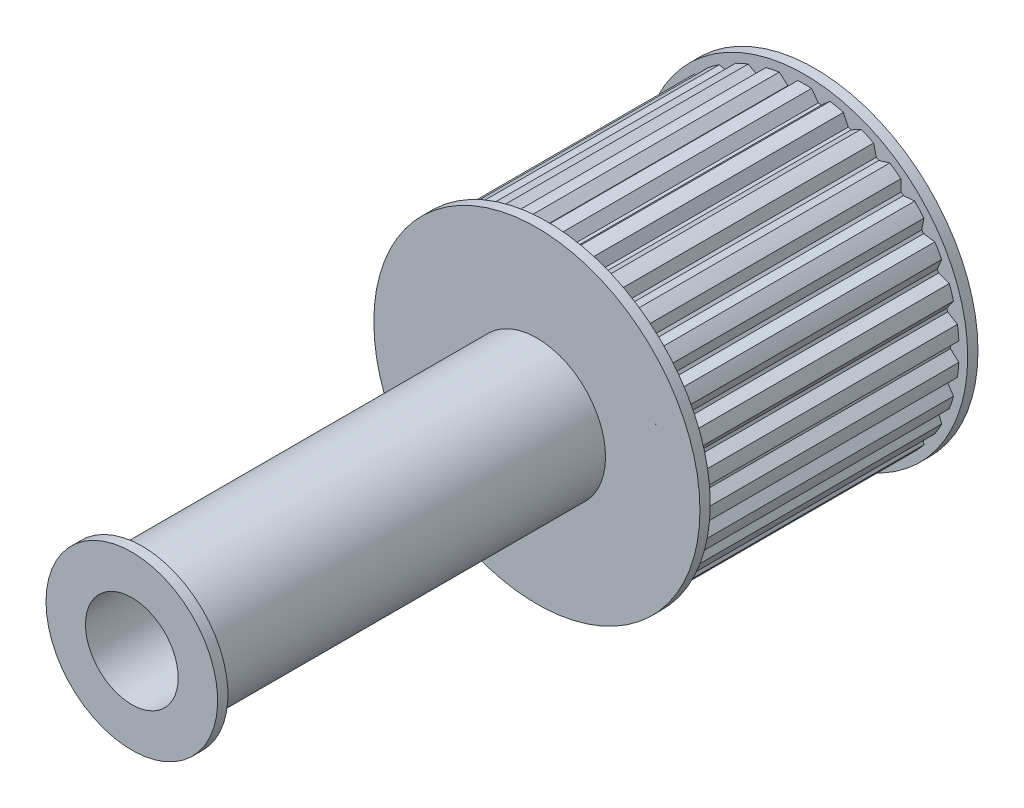
SolidWorks part; units mm, degrees
ref_plane "Front Plane" through (0, 0, 0) normal (0, 0, 1) x (1, 0, 0)
ref_plane "Top Plane" through (0, 0, 0) normal (0, 1, 0) x (1, 0, 0)
ref_plane "Right Plane" through (0, 0, 0) normal (1, 0, 0) x (0, 0, -1)
sketch "Sketch1" plane through (0, 0, 0) normal (0, 0, 1) x (1, 0, 0)
  line L0 (-26.76, 0) -> (36.8516, 0) construction
  line L1 (0, -14.6584) -> (0, 16.5839) construction
  circle A1 centre (0, 0) radius 6.35
  dimension "D2" = 12.7
extrude "Boss-Extrude1" add sketch "Sketch1" along normal blind 0.762
sketch "Sketch3" plane through (0, 0, 0) normal (0, 0, -1) x (-1, 0, 0)
  circle A0 centre (0, 0) radius 5.08
  dimension "D1" = 10.16
extrude "Boss-Extrude2" add sketch "Sketch3" along normal blind 29.21
sketch "Sketch9" plane through (0, 0, -29.21) normal (0, 0, -1) x (-1, 0, 0)
  circle A0 centre (0, 0) radius 5.08
  dimension "D1" = 10.16
curve "Helix/Spiral1" pitch 1.5568 height 28.8008 turns 18.5
sketch "Sketch4" plane through (0, 0, -29.21) normal (0, 0, -1) x (-1, 0, 0)
  circle A0 centre (0, 0.091) radius 12.065
  dimension "D1" = 24.13
extrude "Boss-Extrude3" add sketch "Sketch4" along normal blind 0.762
sketch "Sketch5" plane through (0, 0, -29.972) normal (0, 0, -1) x (-1, 0, 0)
  circle A0 centre (0, 0) radius 10.795
  dimension "D1" = 21.59
extrude "Boss-Extrude4" add sketch "Sketch5" along normal blind 19.05
sketch "Sketch8" plane through (0, 0, -49.022) normal (0, 0, -1) x (-1, 0, 0)
  line L0 (0, 11.43) -> (0, -11.43) construction
  line L1 (-0.508, 11.4187) -> (-1.016, 10.7471)
  line L2 (0.508, 11.4187) -> (1.016, 10.7471)
  line L3 (1.8772, 11.2748) -> (1.2406, 10.7235)
  line L4 (4.1803, 10.6381) -> (3.4431, 10.2312)
  line L5 (6.3008, 9.5365) -> (5.495, 9.2918)
  line L6 (8.1458, 8.0181) -> (7.3068, 7.9462)
  line L7 (9.6349, 6.1493) -> (8.7992, 6.2534)
  line L8 (10.7029, 4.0117) -> (9.9071, 4.2873)
  line L9 (11.3031, 1.6988) -> (10.582, 2.1338)
  line L10 (11.4093, -0.6884) -> (10.7944, -0.1129)
  line L11 (11.0168, -3.0454) -> (10.535, -2.3548)
  line L12 (10.1429, -5.2694) -> (9.8152, -4.4937)
  line L13 (8.8257, -7.2631) -> (8.6665, -6.4362)
  line L14 (7.1227, -8.9393) -> (7.1389, -8.0974)
  line L15 (5.1085, -10.2249) -> (5.2994, -9.4047)
  line L16 (2.871, -11.0636) -> (3.2282, -10.301)
  line L17 (0.508, -11.4187) -> (1.016, -10.7471)
  line L18 (-1.8772, -11.2748) -> (-1.2406, -10.7235)
  line L19 (-4.1803, -10.6381) -> (-3.4431, -10.2312)
  line L20 (-6.3008, -9.5365) -> (-5.495, -9.2918)
  line L21 (-8.1458, -8.0181) -> (-7.3068, -7.9462)
  line L22 (-9.6349, -6.1493) -> (-8.7992, -6.2534)
  line L23 (-10.7029, -4.0117) -> (-9.9071, -4.2873)
  line L24 (-11.3031, -1.6988) -> (-10.582, -2.1338)
  line L25 (-11.4093, 0.6884) -> (-10.7944, 0.1129)
  line L26 (-11.0168, 3.0454) -> (-10.535, 2.3548)
  line L27 (-10.1429, 5.2694) -> (-9.8152, 4.4937)
  line L28 (-8.8257, 7.2631) -> (-8.6665, 6.4362)
  line L29 (-7.1227, 8.9393) -> (-7.1389, 8.0974)
  line L30 (-5.1085, 10.2249) -> (-5.2994, 9.4047)
  line L31 (-2.871, 11.0636) -> (-3.2282, 10.301)
  line L32 (2.871, 11.0636) -> (3.2282, 10.301)
  line L33 (5.1085, 10.2249) -> (5.2994, 9.4047)
  line L34 (7.1227, 8.9393) -> (7.1389, 8.0974)
  line L35 (8.8257, 7.2631) -> (8.6665, 6.4362)
  line L36 (10.1429, 5.2694) -> (9.8152, 4.4937)
  line L37 (11.0168, 3.0454) -> (10.535, 2.3548)
  line L38 (11.4093, 0.6884) -> (10.7944, 0.1129)
  line L39 (11.3031, -1.6988) -> (10.582, -2.1338)
  line L40 (10.7029, -4.0117) -> (9.9071, -4.2873)
  line L41 (9.6349, -6.1493) -> (8.7992, -6.2534)
  line L42 (8.1458, -8.0181) -> (7.3068, -7.9462)
  line L43 (6.3008, -9.5365) -> (5.495, -9.2918)
  line L44 (4.1803, -10.6381) -> (3.4431, -10.2312)
  line L45 (1.8772, -11.2748) -> (1.2406, -10.7235)
  line L46 (-0.508, -11.4187) -> (-1.016, -10.7471)
  line L47 (-2.871, -11.0636) -> (-3.2282, -10.301)
  line L48 (-5.1085, -10.2249) -> (-5.2994, -9.4047)
  line L49 (-7.1227, -8.9393) -> (-7.1389, -8.0974)
  line L50 (-8.8257, -7.2631) -> (-8.6665, -6.4362)
  line L51 (-10.1429, -5.2694) -> (-9.8152, -4.4937)
  line L52 (-11.0168, -3.0454) -> (-10.535, -2.3548)
  line L53 (-11.4093, -0.6884) -> (-10.7944, -0.1129)
  line L54 (-11.3031, 1.6988) -> (-10.582, 2.1338)
  line L55 (-10.7029, 4.0117) -> (-9.9071, 4.2873)
  line L56 (-9.6349, 6.1493) -> (-8.7992, 6.2534)
  line L57 (-8.1458, 8.0181) -> (-7.3068, 7.9462)
  line L58 (-6.3008, 9.5365) -> (-5.495, 9.2918)
  line L59 (-4.1803, 10.6381) -> (-3.4431, 10.2312)
  line L60 (-1.8772, 11.2748) -> (-1.2406, 10.7235)
  circle A0 centre (0, 0) radius 11.43
  circle A1 centre (0, 0) radius 10.795
  point P69 (0, 0)
  point P129 (0, 0)
  circle M4 centre (0, 0) radius 10.795
  dimension "D1" = 22.86
  dimension "D2" = 21.59
  dimension "D3" = 0.508
  dimension "D4" = 1.016
  dimension "D5" = 30
  dimension "D6" = 30
extrude "Boss-Extrude6" add sketch "Sketch8" against normal up to surface (19.05 mm away) contours L0 A0 L1 A1 | A0 L0 L2 M4 | L32 A0 L3 M4 | L33 A0 L4 M4 | L34 A0 L5 M4 | L35 A0 L6 M4 | L60 A0 L31 M4 | L59 A0 L30 M4 | L36 A0 L7 M4 | L37 A0 L8 M4 | L38 A0 L9 M4 | L39 A0 L10 M4 | L40 A0 L11 M4 | L41 A0 L12 M4 | L42 A0 L13 M4 | L43 A0 L14 M4 | L44 A0 L15 M4 | L45 A0 L16 M4 | A1 L0 A0 L17 | L0 L46 A0 M4 | L47 A0 L18 M4 | L48 A0 L19 M4 | L49 A0 L20 M4 | L50 A0 L21 M4 | L51 A0 L22 M4 | L52 A0 L23 M4 | L53 A0 L24 M4 | L54 A0 L25 M4 | L55 A0 L26 M4 | L56 A0 L27 M4 | L57 A0 L28 M4 | L58 A0 L29 M4 up to face at (-12.065, 0.091, -29.972)
sketch "Sketch6" plane through (0, 0, -49.022) normal (0, 0, -1) x (-1, 0, 0)
  circle A0 centre (0, 0) radius 12.065
  dimension "D1" = 24.13
extrude "Boss-Extrude5" add sketch "Sketch6" along normal blind 0.762
sketch "Sketch7" plane through (0, 0, -49.784) normal (0, 0, -1) x (-1, 0, 0)
  circle A0 centre (0, 0) radius 3.429
  dimension "D1" = 6.858
extrude "Cut-Extrude1" cut sketch "Sketch7" against normal up to next
